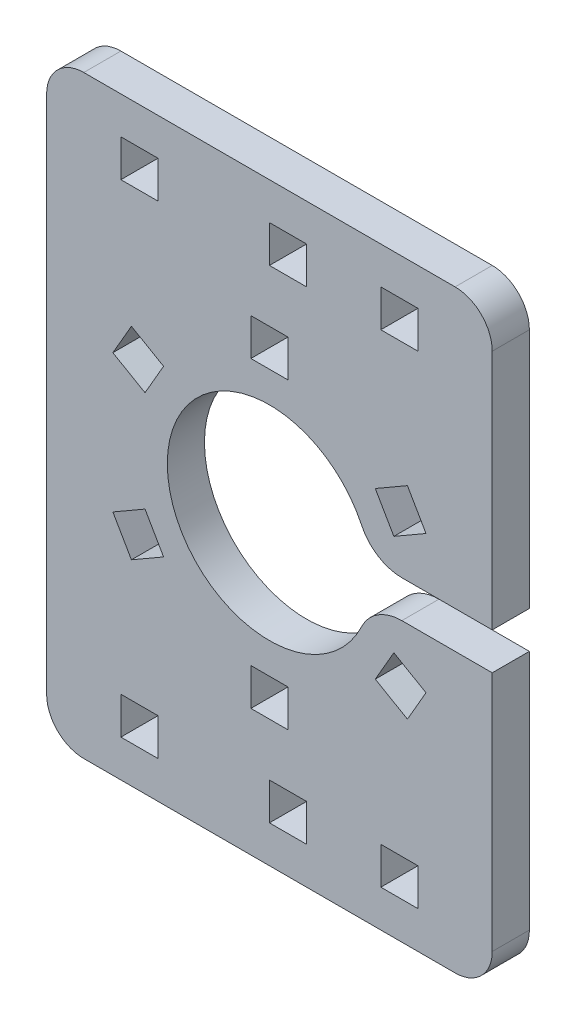
SolidWorks part; units mm, degrees
ref_plane "Plan de face" through (0, 0, 0) normal (0, 0, 1) x (1, 0, 0)
ref_plane "Plan de dessus" through (0, 0, 0) normal (0, 1, 0) x (1, 0, 0)
ref_plane "Plan de droite" through (0, 0, 0) normal (1, 0, 0) x (0, 0, -1)
sketch "Esquisse1" plane through (0, 0, 0) normal (0, 0, 1) x (1, 0, 0)
  line L0 (-55, 80) -> (-5, 80)
  line L1 (-10, 70) -> (-10, 75)
  line L2 (-50, 10) -> (-45, 10)
  line L3 (-50, 10) -> (-50, 5)
  line L4 (-50, 5) -> (-45, 5)
  line L5 (-45, 10) -> (-45, 5)
  line L6 (-30, 10) -> (-25, 10)
  line L7 (-30, 10) -> (-30, 5)
  line L8 (-30, 5) -> (-25, 5)
  line L9 (-55, 0) -> (-5, 0)
  line L10 (-25, 10) -> (-25, 5)
  line L11 (-15, 10) -> (-10, 10)
  line L12 (-15, 10) -> (-15, 5)
  line L13 (-15, 5) -> (-10, 5)
  line L14 (-10, 10) -> (-10, 5)
  line L15 (-15, 75) -> (-10, 75)
  line L16 (-15, 70) -> (-15, 75)
  line L17 (-60, 40) -> (0, 40) construction
  line L18 (-15, 70) -> (-10, 70)
  line L19 (-25, 70) -> (-25, 75)
  line L20 (-30, 75) -> (-25, 75)
  line L21 (-30, 70) -> (-30, 75)
  line L22 (-30, 70) -> (-25, 70)
  line L23 (-45, 70) -> (-45, 75)
  line L24 (-50, 75) -> (-45, 75)
  line L25 (-50, 70) -> (-50, 75)
  line L26 (-50, 70) -> (-45, 70)
  line L43 (-60, 75) -> (-60, 5)
  line L44 (-30, 57.9) -> (-30, 40) construction
  line L45 (-32.5, 62.9) -> (-27.5, 62.9)
  line L46 (-32.5, 62.9) -> (-32.5, 57.9)
  line L47 (-32.5, 57.9) -> (-27.5, 57.9)
  line L48 (-27.5, 62.9) -> (-27.5, 57.9)
  line L49 (-11.418, 53.6151) -> (-8.918, 49.2849)
  line L50 (-11.418, 53.6151) -> (-15.7481, 51.1151)
  line L51 (-15.7481, 51.1151) -> (-13.2481, 46.7849)
  line L52 (-8.918, 49.2849) -> (-13.2481, 46.7849)
  line L53 (-8.918, 30.7151) -> (-11.418, 26.3849)
  line L54 (-8.918, 30.7151) -> (-13.2481, 33.2151)
  line L55 (-13.2481, 33.2151) -> (-15.7481, 28.8849)
  line L56 (-11.418, 26.3849) -> (-15.7481, 28.8849)
  line L57 (-27.5, 17.1) -> (-32.5, 17.1)
  line L58 (-27.5, 17.1) -> (-27.5, 22.1)
  line L59 (-27.5, 22.1) -> (-32.5, 22.1)
  line L60 (-32.5, 17.1) -> (-32.5, 22.1)
  line L61 (-48.582, 26.3849) -> (-51.082, 30.7151)
  line L62 (-48.582, 26.3849) -> (-44.2519, 28.8849)
  line L63 (-44.2519, 28.8849) -> (-46.7519, 33.2151)
  line L64 (-51.082, 30.7151) -> (-46.7519, 33.2151)
  line L65 (-51.082, 49.2849) -> (-48.582, 53.6151)
  line L66 (-51.082, 49.2849) -> (-46.7519, 46.7849)
  line L67 (-46.7519, 46.7849) -> (-44.2519, 51.1151)
  line L68 (-48.582, 53.6151) -> (-44.2519, 51.1151)
  line L69 (0, 5) -> (0, 37.5)
  line L70 (0, 42.5) -> (-12.1727, 42.5)
  line L71 (-12.1727, 37.5) -> (0, 37.5)
  line L72 (0, 42.5) -> (0, 75)
  arc A0 (-55, 0) -> (-60, 5) centre (-55, 5) cw
  arc A1 (-17.5886, 45.9177) -> (-17.5886, 34.0823) centre (-30, 40) ccw
  arc A2 (-12.1727, 37.5) -> (-17.5886, 34.0823) centre (-12.1727, 31.5) ccw
  arc A3 (-12.1727, 42.5) -> (-17.5886, 45.9177) centre (-12.1727, 48.5) cw
  arc A4 (-5, 0) -> (0, 5) centre (-5, 5) ccw
  arc A5 (-5, 80) -> (0, 75) centre (-5, 75) cw
  arc A6 (-55, 80) -> (-60, 75) centre (-55, 75) ccw
  point P19 (-60, 0)
  point P25 (0, 0)
  point P29 (0, 80)
  point P34 (-60, 80)
  point P82 (-30, 40)
  dimension "D9" = 10
  dimension "D10" = 27.5
  dimension "D17" = 6
  dimension "D18" = 30
  dimension "D14" = 5
  dimension "D2" = 60
  dimension "D3" = 5
  dimension "D4" = 10
  dimension "D5" = 5
  dimension "D6" = 80
  dimension "D7" = 15
  dimension "D8" = 5
  dimension "D11" = 17.9
  dimension "D12" = 5
  dimension "D13" = 6
  dimension "D15" = 5
  dimension "D16" = 5
extrude "Boss.-Extru.1" add sketch "Esquisse1" along normal blind 5
